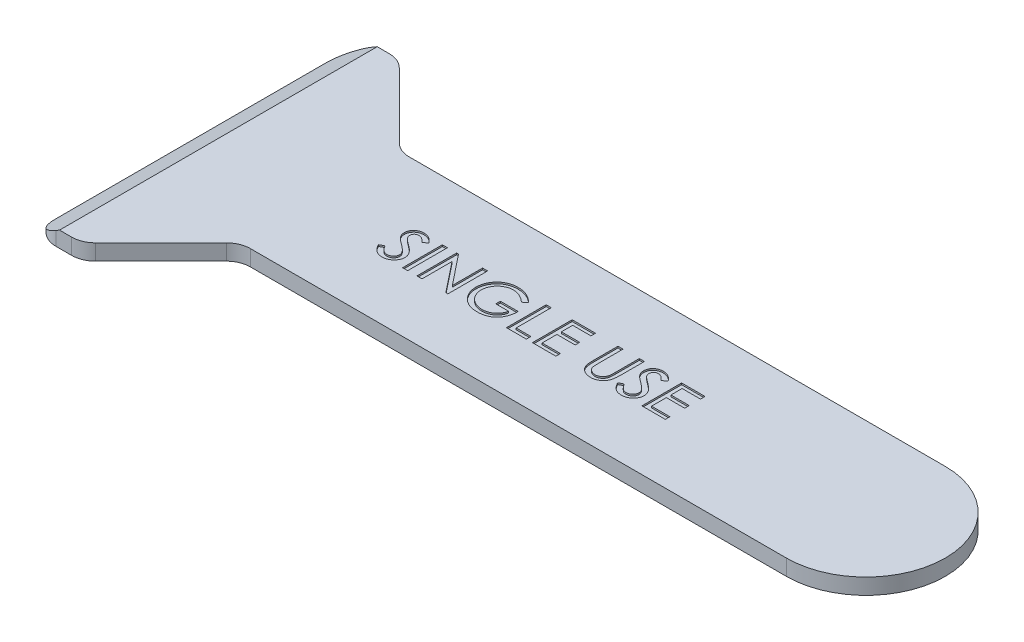
SolidWorks part; units mm, degrees
ref_plane "Front Plane" through (0, 0, 0) normal (0, 0, 1) x (1, 0, 0)
ref_plane "Top Plane" through (0, 0, 0) normal (0, 1, 0) x (1, 0, 0)
ref_plane "Right Plane" through (0, 0, 0) normal (1, 0, 0) x (0, 0, -1)
sketch "Sketch1" plane through (0, 0, 0) normal (0, 1, 0) x (1, 0, 0)
  line L0 (3, 0) -> (5, 0)
  line L1 (7.1213, 0.8787) -> (15.364, 9.1213)
  line L2 (17.4853, 10) -> (85, 10)
  line L3 (85, 30) -> (17.4853, 30)
  line L4 (15.364, 30.8787) -> (7.1213, 39.1213)
  line L5 (5, 40) -> (3, 40)
  line L6 (0, 37) -> (0, 3)
  line L7 (0, 20) -> (85, 20) construction
  arc A0 (85, 10) -> (85, 30) centre (85, 20) ccw
  arc A1 (0, 3) -> (3, 0) centre (3, 3) ccw
  arc A2 (0, 37) -> (3, 40) centre (3, 37) cw
  arc A3 (15.364, 9.1213) -> (17.4853, 10) centre (17.4853, 7) cw
  arc A4 (17.4853, 30) -> (15.364, 30.8787) centre (17.4853, 33) cw
  arc A5 (5, 0) -> (7.1213, 0.8787) centre (5, 3) ccw
  arc A6 (7.1213, 39.1213) -> (5, 40) centre (5, 37) ccw
  point P14 (0, 0)
  point P17 (0, 40)
  point P20 (16.2426, 10)
  point P23 (16.2426, 30)
  dimension "D2" = 3
  dimension "D5" = 3
  dimension "D1" = 95
  dimension "D3" = 20
  dimension "D4" = 40
  dimension "D6" = 2
  dimension "D7" = 135
extrude "Boss-Extrude1" add sketch "Sketch1" along normal blind 2
sketch "Sketch2" plane through (0, 2, 0) normal (0, 1, 0) x (1, 0, 0)
  text T0 "SINGLE USE" font "Century Gothic" height 5
  dimension "D1" = 25
  dimension "D2" = 17.5
extrude "Cut-Extrude1" cut sketch "Sketch2" against normal blind 0.2
sketch "Sketch3" plane through (0, 0, 0) normal (0, 0, 1) x (1, 0, 0)
  line L0 (0, 0) -> (8.6603, 5)
  line L1 (8.6603, 5) -> (0, 5)
  line L2 (0, 5) -> (0, 0)
  dimension "D1" = 5
  dimension "D2" = 60
extrude "Cut-Extrude2" cut sketch "Sketch3" against normal through all
